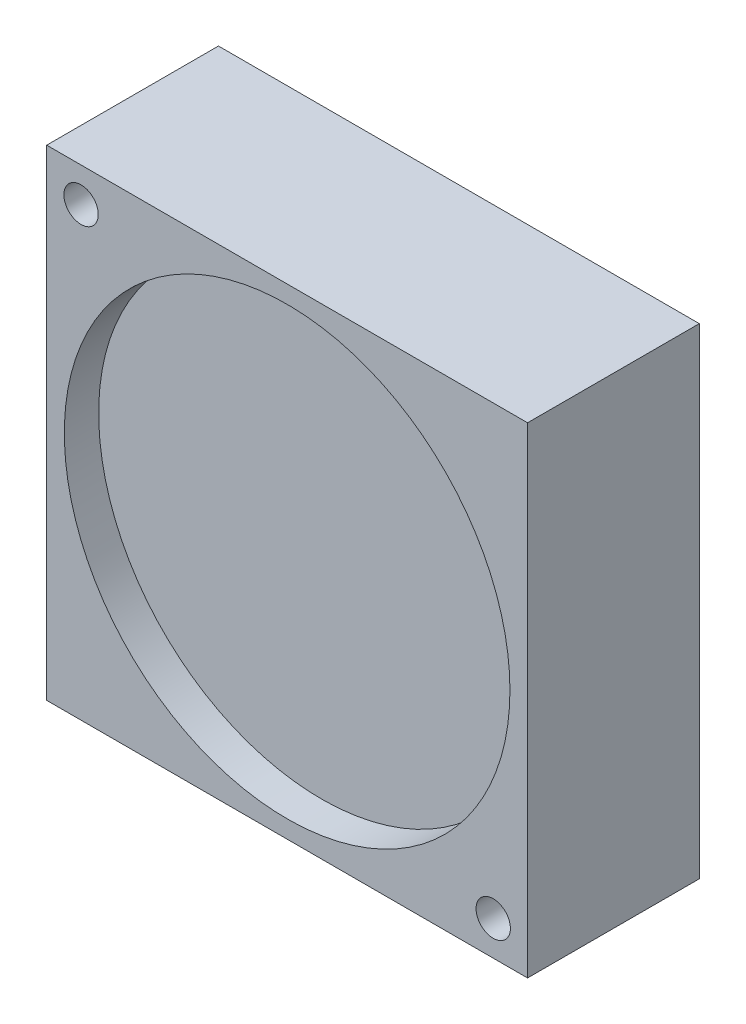
SolidWorks part; units mm, degrees
ref_plane "前视基准面" through (0, 0, 0) normal (0, 0, 1) x (1, 0, 0)
ref_plane "上视基准面" through (0, 0, 0) normal (0, 1, 0) x (1, 0, 0)
ref_plane "右视基准面" through (0, 0, 0) normal (1, 0, 0) x (0, 0, -1)
other "Configuration Table"
sketch "草图1" plane through (0, 0, 0) normal (0, 0, 1) x (1, 0, 0)
  line L1 (14, -14) -> (-14, -14)
  line L2 (14, -14) -> (14, 14)
  line L3 (14, 14) -> (-14, 14)
  line L4 (-14, -14) -> (-14, 14)
  line L5 (14, -14) -> (-14, 14) construction
  line L6 (14, 14) -> (-14, -14) construction
  circle A0 centre (12, -12) radius 1
  circle A1 centre (-12, 12) radius 1
  point P0 (0, 0)
  dimension "D3" = 2
  dimension "D4" = 2
  dimension "D5" = 2
  dimension "D6" = 2
  dimension "D1" = 28
  dimension "D2" = 28
extrude "凸台-拉伸1" add sketch "草图1" along normal blind 10
sketch "草图2" plane through (0, 0, 10) normal (0, 0, 1) x (1, 0, 0)
  circle A0 centre (0, 0) radius 12.9747
extrude "切除-拉伸1" cut sketch "草图2" against normal blind 2
